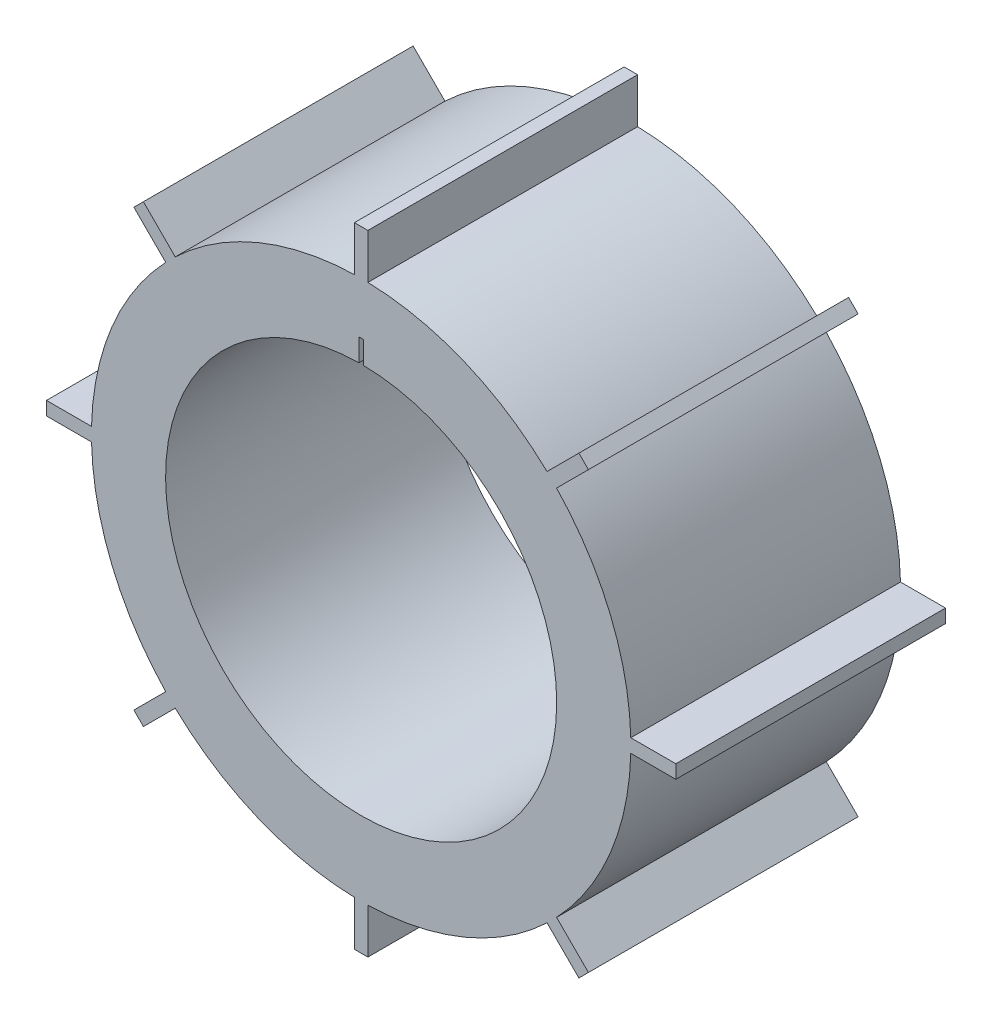
SolidWorks part; units mm, degrees
ref_plane "Front Plane" through (0, 0, 0) normal (0, 0, 1) x (1, 0, 0)
ref_plane "Top Plane" through (0, 0, 0) normal (0, 1, 0) x (1, 0, 0)
ref_plane "Right Plane" through (0, 0, 0) normal (1, 0, 0) x (0, 0, -1)
ref_plane "Plane1"
sketch "Sketch1" plane through (0, 0, 0) normal (0, 0, 1) x (1, 0, 0)
  circle A0 centre (0, 0) radius 60
  circle A1 centre (0, 0) radius 43.5
  dimension "D1" = 87
  dimension "D2" = 120
extrude "Extrusion1" add sketch "Sketch1" along normal blind 60 contours A0 A1
ref_plane "Plane2"
sketch "Sketch2" plane through (0, 0, 60) normal (0, 0, 1) x (1, 0, 0)
  line L0 (33.701, 61.3718) -> (28.6916, 52.6953)
  line L1 (-1.5, 70) -> (-1.5, 59.9812)
  line L2 (1.5, 70) -> (1.5, 59.9812)
  line L4 (-1.5, 70) -> (1.5, 70)
  line L5 (33.701, 61.3718) -> (36.299, 59.8718)
  line L6 (36.299, 59.8718) -> (31.2897, 51.1953)
  line L7 (59.8718, 36.299) -> (51.1953, 31.2897)
  line L8 (59.8718, 36.299) -> (61.3718, 33.701)
  line L9 (61.3718, 33.701) -> (52.6953, 28.6916)
  line L10 (70, 1.5) -> (59.9812, 1.5)
  line L11 (70, 1.5) -> (70, -1.5)
  line L12 (70, -1.5) -> (59.9812, -1.5)
  line L13 (61.3718, -33.701) -> (52.6953, -28.6916)
  line L14 (61.3718, -33.701) -> (59.8718, -36.299)
  line L15 (59.8718, -36.299) -> (51.1953, -31.2897)
  line L16 (36.299, -59.8718) -> (31.2897, -51.1953)
  line L17 (36.299, -59.8718) -> (33.701, -61.3718)
  line L18 (33.701, -61.3718) -> (28.6916, -52.6953)
  line L19 (1.5, -70) -> (1.5, -59.9812)
  line L20 (1.5, -70) -> (-1.5, -70)
  line L21 (-1.5, -70) -> (-1.5, -59.9812)
  line L22 (-33.701, -61.3718) -> (-28.6916, -52.6953)
  line L23 (-33.701, -61.3718) -> (-36.299, -59.8718)
  line L24 (-36.299, -59.8718) -> (-31.2897, -51.1953)
  line L25 (-59.8718, -36.299) -> (-51.1953, -31.2897)
  line L26 (-59.8718, -36.299) -> (-61.3718, -33.701)
  line L27 (-61.3718, -33.701) -> (-52.6953, -28.6916)
  line L28 (-70, -1.5) -> (-59.9812, -1.5)
  line L29 (-70, -1.5) -> (-70, 1.5)
  line L30 (-70, 1.5) -> (-59.9812, 1.5)
  line L31 (-61.3718, 33.701) -> (-52.6953, 28.6916)
  line L32 (-61.3718, 33.701) -> (-59.8718, 36.299)
  line L33 (-59.8718, 36.299) -> (-51.1953, 31.2897)
  line L34 (-36.299, 59.8718) -> (-31.2897, 51.1953)
  line L35 (-36.299, 59.8718) -> (-33.701, 61.3718)
  line L36 (-33.701, 61.3718) -> (-28.6916, 52.6953)
  arc A0 (1.5, 59.9812) -> (-1.5, 59.9812) centre (0, 0) ccw
  arc A1 (31.2897, 51.1953) -> (28.6916, 52.6953) centre (0, 0) ccw
  arc A2 (52.6953, 28.6916) -> (51.1953, 31.2897) centre (0, 0) ccw
  arc A3 (59.9812, -1.5) -> (59.9812, 1.5) centre (0, 0) ccw
  arc A4 (51.1953, -31.2897) -> (52.6953, -28.6916) centre (0, 0) ccw
  arc A5 (28.6916, -52.6953) -> (31.2897, -51.1953) centre (0, 0) ccw
  arc A6 (-1.5, -59.9812) -> (1.5, -59.9812) centre (0, 0) ccw
  arc A7 (-31.2897, -51.1953) -> (-28.6916, -52.6953) centre (0, 0) ccw
  arc A8 (-52.6953, -28.6916) -> (-51.1953, -31.2897) centre (0, 0) ccw
  arc A9 (-59.9812, 1.5) -> (-59.9812, -1.5) centre (0, 0) ccw
  arc A10 (-51.1953, 31.2897) -> (-52.6953, 28.6916) centre (0, 0) ccw
  arc A11 (-28.6916, 52.6953) -> (-31.2897, 51.1953) centre (0, 0) ccw
  point P52 (0, 0)
  dimension "D1" = 12
ref_plane "Plane3"
sketch "Sketch3" plane through (0, 0, 60) normal (0, 0, 1) x (1, 0, 0)
  line L0 (-0.5, 48.5) -> (-0.5, 43.4971)
  line L1 (0.5, 43.4971) -> (0.5, 48.5)
  line L2 (0.5, 48.5) -> (-0.5, 48.5)
  arc A0 (0.5, 43.4971) -> (-0.5, 43.4971) centre (0, 0) ccw
extrude "Extrusion3" cut sketch "Sketch3" against normal blind 60
sketch "Sketch4" plane through (0, 0, 60) normal (0, 0, 1) x (1, 0, 0)
  line L0 (41.3525, 43.4738) -> (48.4368, 50.5581)
  line L1 (48.4368, 50.5581) -> (50.5581, 48.4368)
  line L2 (43.4738, 41.3525) -> (50.5581, 48.4368)
  line L3 (1.5, 59.9812) -> (1.5, 70)
  line L4 (59.9812, 1.5) -> (70, 1.5)
  line L5 (-1.5, 59.9812) -> (-1.5, 70)
  line L6 (-1.5, 70) -> (1.5, 70)
  line L7 (70, 1.5) -> (70, -1.5)
  line L8 (59.9812, -1.5) -> (70, -1.5)
  line L9 (43.4738, -41.3525) -> (50.5581, -48.4368)
  line L10 (50.5581, -48.4368) -> (48.4368, -50.5581)
  line L11 (41.3525, -43.4738) -> (48.4368, -50.5581)
  line L12 (1.5, -59.9812) -> (1.5, -70)
  line L13 (1.5, -70) -> (-1.5, -70)
  line L14 (-1.5, -59.9812) -> (-1.5, -70)
  line L15 (-41.3525, -43.4738) -> (-48.4368, -50.5581)
  line L16 (-48.4368, -50.5581) -> (-50.5581, -48.4368)
  line L17 (-43.4738, -41.3525) -> (-50.5581, -48.4368)
  line L18 (-59.9812, -1.5) -> (-70, -1.5)
  line L19 (-70, -1.5) -> (-70, 1.5)
  line L20 (-59.9812, 1.5) -> (-70, 1.5)
  line L21 (-43.4738, 41.3525) -> (-50.5581, 48.4368)
  line L22 (-50.5581, 48.4368) -> (-48.4368, 50.5581)
  line L23 (-41.3525, 43.4738) -> (-48.4368, 50.5581)
  arc A1 (1.5, 59.9812) -> (-1.5, 59.9812) centre (0, 0) ccw
  arc A2 (43.4738, 41.3525) -> (41.3525, 43.4738) centre (0, 0) ccw
  arc A3 (59.9812, -1.5) -> (59.9812, 1.5) centre (0, 0) ccw
  arc A4 (41.3525, -43.4738) -> (43.4738, -41.3525) centre (0, 0) ccw
  arc A5 (-1.5, -59.9812) -> (1.5, -59.9812) centre (0, 0) ccw
  arc A6 (-43.4738, -41.3525) -> (-41.3525, -43.4738) centre (0, 0) ccw
  arc A7 (-59.9812, 1.5) -> (-59.9812, -1.5) centre (0, 0) ccw
  arc A8 (-41.3525, 43.4738) -> (-43.4738, 41.3525) centre (0, 0) ccw
  point P39 (0, 0)
  dimension "D1" = 8
extrude "Boss-Extrude1" add sketch "Sketch4" against normal through all
